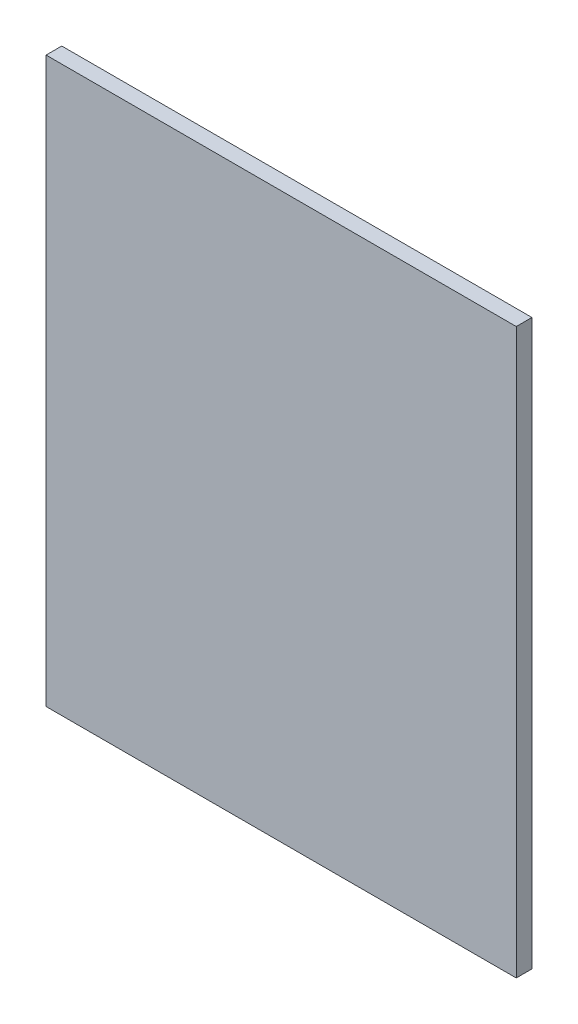
SolidWorks part; units mm, degrees
material "Cedar"
ref_plane "Front Plane" through (0, 0, 0) normal (0, 0, 1) x (1, 0, 0)
ref_plane "Top Plane" through (0, 0, 0) normal (0, 1, 0) x (1, 0, 0)
ref_plane "Right Plane" through (0, 0, 0) normal (1, 0, 0) x (0, 0, -1)
sketch "Sketch1" plane through (0, 0, 0) normal (0, 0, 1) x (1, 0, 0)
  line L1 (0, 0) -> (190.5, 0)
  line L2 (0, 0) -> (0, 228.6)
  line L3 (0, 228.6) -> (190.5, 228.6)
  line L4 (190.5, 0) -> (190.5, 228.6)
  dimension "D1" = 190.5
  dimension "D2" = 228.6
extrude "Boss-Extrude1" add sketch "Sketch1" along normal blind 6.35
ref_plane "Plane1" through (0, 0, 3.175) normal (0, 0, 1) x (1, 0, 0)
ref_plane "Plane2" through (95.25, 0, 0) normal (1, 0, 0) x (0, 0, -1)
